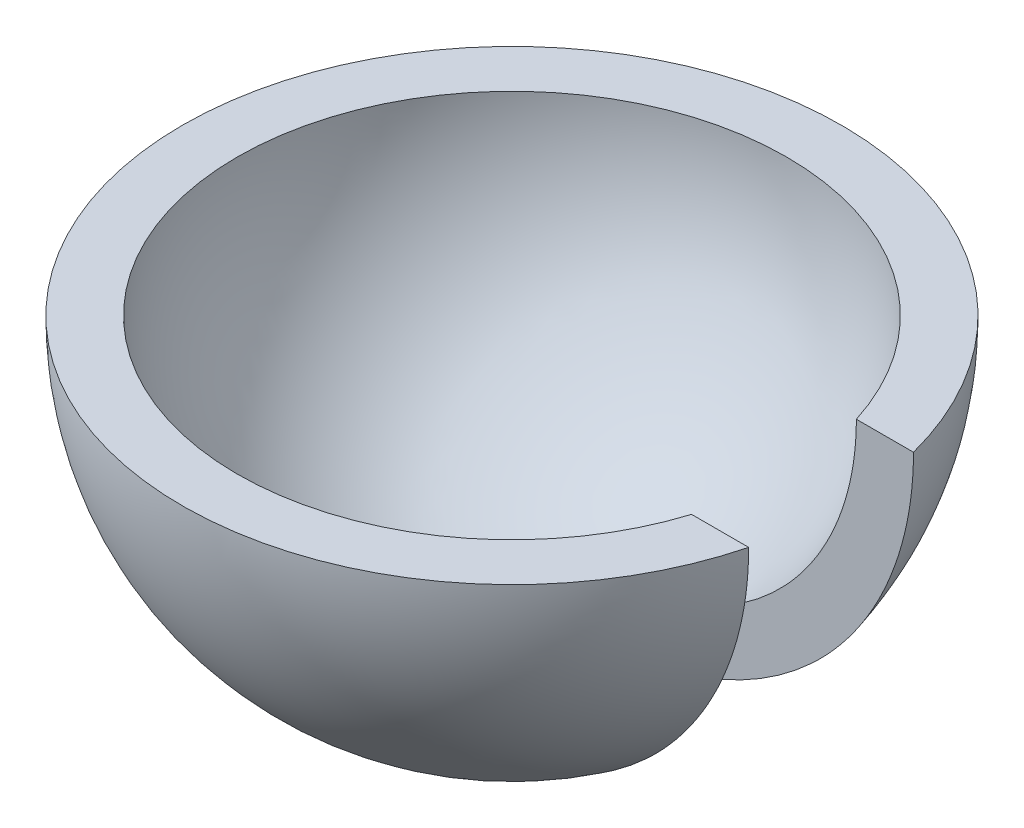
SolidWorks part; units mm, degrees
ref_plane "Front Plane" through (0, 0, 0) normal (0, 0, 1) x (1, 0, 0)
ref_plane "Top Plane" through (0, 0, 0) normal (0, 1, 0) x (1, 0, 0)
ref_plane "Right Plane" through (0, 0, 0) normal (1, 0, 0) x (0, 0, -1)
sketch "Sketch1" plane through (0, 0, 0) normal (0, 1, 0) x (1, 0, 0)
  line L0 (-5, 0) -> (-6, 0)
  line L1 (5, 0) -> (6, 0)
  arc A0 (5, 0) -> (-5, 0) centre (0, 0) ccw
  arc A1 (6, 0) -> (-6, 0) centre (0, 0) ccw
revolve "Revolve1" add sketch "Sketch1" angle 180 about L0
sketch "Sketch2" plane through (0, 0, 0) normal (0, 1, 0) x (1, 0, 0)
  line L1 (0, 1.5) -> (6, 1.5)
  line L2 (0, 1.5) -> (0, -1.5)
  line L3 (0, -1.5) -> (6, -1.5)
  line L4 (6, 1.5) -> (6, -1.5)
  circle A0 centre (0, 0) radius 6 construction
  point P4 (0, 0)
  dimension "D1" = 3
extrude "Cut-Extrude1" cut sketch "Sketch2" against normal through all
